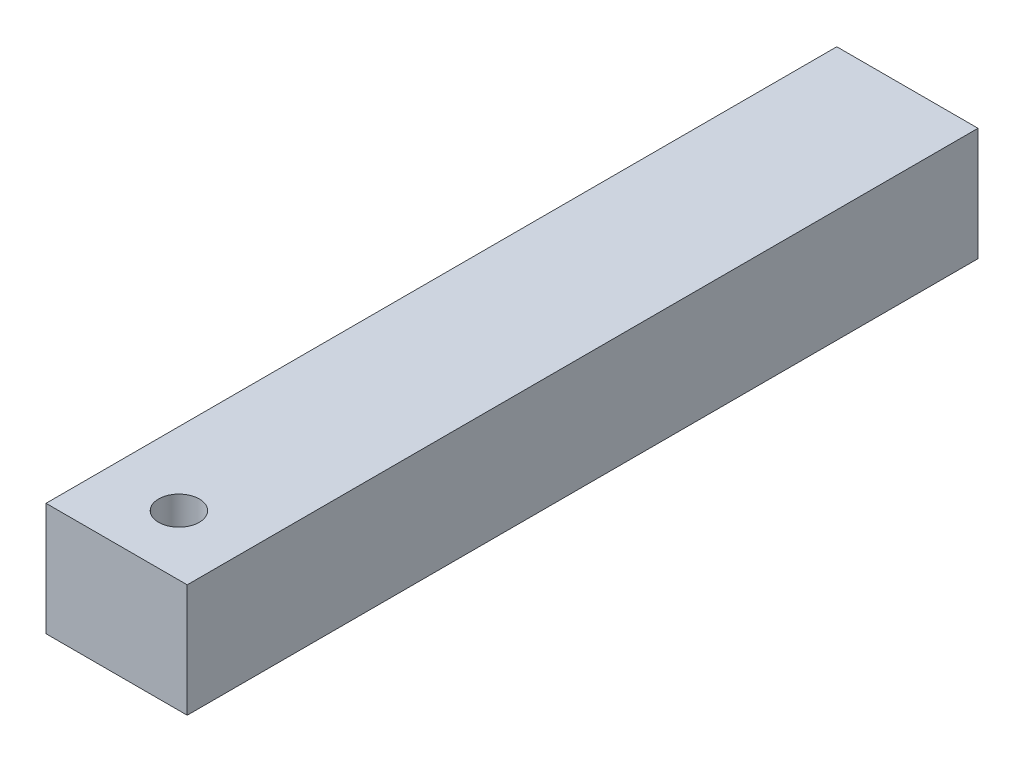
SolidWorks part; units mm, degrees
ref_plane "Front Plane" through (0, 0, 0) normal (0, 0, 1) x (1, 0, 0)
ref_plane "Top Plane" through (0, 0, 0) normal (0, 1, 0) x (1, 0, 0)
ref_plane "Right Plane" through (0, 0, 0) normal (1, 0, 0) x (0, 0, -1)
sketch "Sketch1" plane through (0, 0, 0) normal (0, 1, 0) x (1, 0, 0)
  line L1 (0, 0) -> (31.75, 0)
  line L2 (0, 0) -> (0, -177.8)
  line L3 (0, -177.8) -> (31.75, -177.8)
  line L4 (31.75, 0) -> (31.75, -177.8)
  dimension "D1" = 31.75
  dimension "D2" = 177.8
extrude "Boss-Extrude1" add sketch "Sketch1" along normal blind 25.4
sketch "Sketch2" plane through (0, 25.4, 0) normal (0, 1, 0) x (1, 0, 0)
  circle A0 centre (16.3718, -164.2879) radius 4.5686
  point P2 (16.3718, -164.2879)
extrude "Cut-Extrude1" cut sketch "Sketch2" against normal blind 25.4
